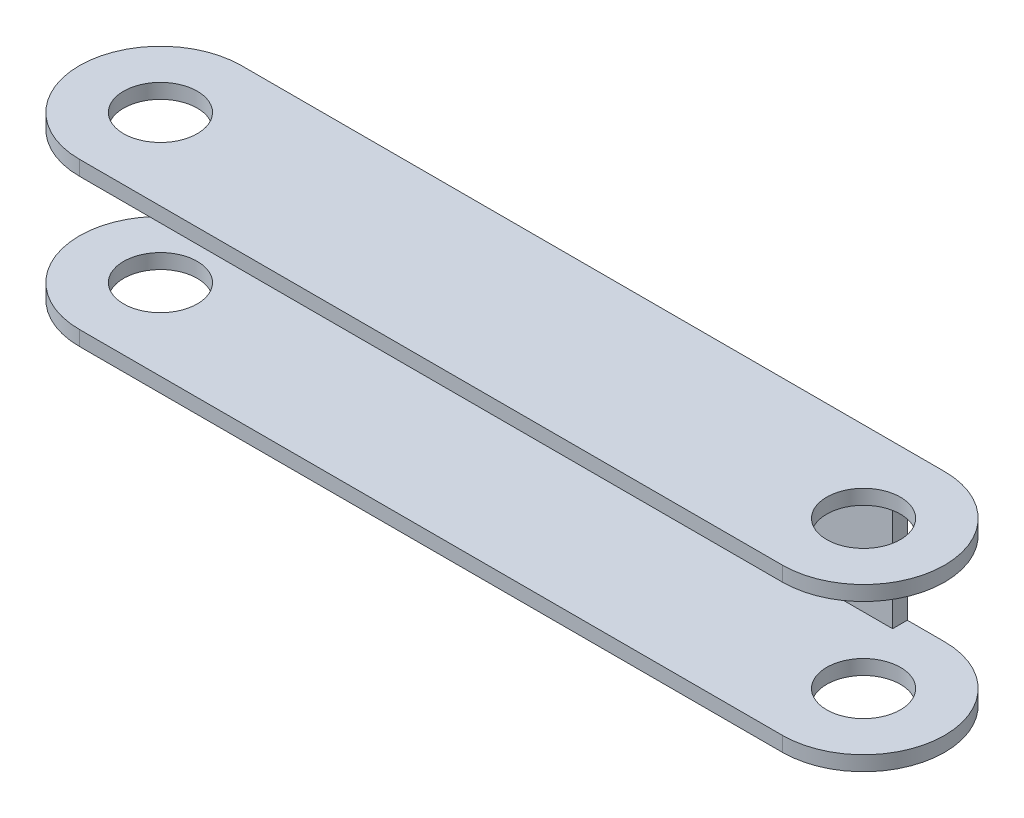
SolidWorks part; units mm, degrees
material "AISI 1045 Steel, cold drawn"
ref_plane "Front Plane" through (0, 0, 0) normal (0, 0, 1) x (1, 0, 0)
ref_plane "Top Plane" through (0, 0, 0) normal (0, 1, 0) x (1, 0, 0)
ref_plane "Right Plane" through (0, 0, 0) normal (1, 0, 0) x (0, 0, -1)
sketch "Sketch1" plane through (0, 0, 0) normal (0, 1, 0) x (1, 0, 0)
  line L1 (-47.7, 11) -> (47.7, 11)
  line L2 (-47.7, -11) -> (47.7, -11)
  arc A0 (-47.7, 11) -> (-47.7, -11) centre (-47.7, 0) ccw
  arc A1 (47.7, -11) -> (47.7, 11) centre (47.7, 0) ccw
  circle A2 centre (47.7, 0) radius 5
  circle A3 centre (-47.7, 0) radius 5
  point P4 (0, 0)
extrude "Boss-Extrude1" add sketch "Sketch1" along normal blind 2
sketch "Sketch2" plane through (0, 2, 0) normal (0, 1, 0) x (1, 0, 0)
  line L0 (47.7, 11) -> (-47.7, 11) construction
  line L1 (-37.3591, 11) -> (42.6409, 11)
  line L2 (-37.3591, 11) -> (-37.3591, 9)
  line L3 (-37.3591, 9) -> (42.6409, 9)
  line L4 (42.6409, 11) -> (42.6409, 9)
  dimension "D1" = 2
  dimension "D2" = 80
extrude "Boss-Extrude2" add sketch "Sketch2" along normal blind 9
mirror "Mirror1" about plane through (0, 11, 0) normal (0, 1, 0) of bodies 102
sketch "Sketch3" plane through (0, 0, -11) normal (0, 0, -1) x (-1, 0, 0)
  line L0 (-58.7, 22) -> (-58.7, 0)
